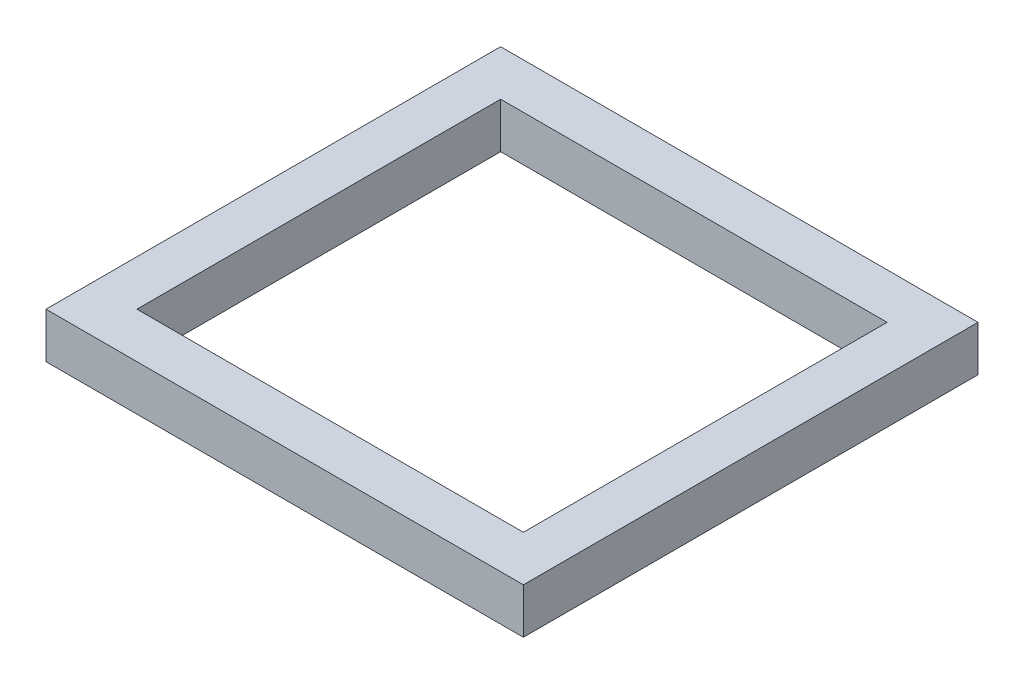
SolidWorks part; units mm, degrees
ref_plane "Front Plane" through (0, 0, 0) normal (0, 0, 1) x (1, 0, 0)
ref_plane "Top Plane" through (0, 0, 0) normal (0, 1, 0) x (1, 0, 0)
ref_plane "Right Plane" through (0, 0, 0) normal (1, 0, 0) x (0, 0, -1)
sketch "Sketch1" plane through (0, 0, 0) normal (0, 1, 0) x (1, 0, 0)
  line L1 (-107.95, -101.6) -> (107.95, -101.6)
  line L2 (-107.95, -101.6) -> (-107.95, 101.6)
  line L3 (-107.95, 101.6) -> (107.95, 101.6)
  line L4 (107.95, -101.6) -> (107.95, 101.6)
  line L5 (-107.95, -101.6) -> (107.95, 101.6) construction
  line L6 (-107.95, 101.6) -> (107.95, -101.6) construction
  line L7 (-133.35, -127) -> (133.35, -127)
  line L8 (-133.35, -127) -> (-133.35, 127)
  line L9 (-133.35, 127) -> (133.35, 127)
  line L10 (133.35, -127) -> (133.35, 127)
  line L11 (-133.35, -127) -> (133.35, 127) construction
  line L12 (-133.35, 127) -> (133.35, -127) construction
  point P0 (0, 0)
  point P6 (0, 0)
  dimension "D1" = 215.9
  dimension "D2" = 203.2
  dimension "D3" = 25.4
  dimension "D4" = 25.4
extrude "Boss-Extrude1" add sketch "Sketch1" along normal blind 25.4
